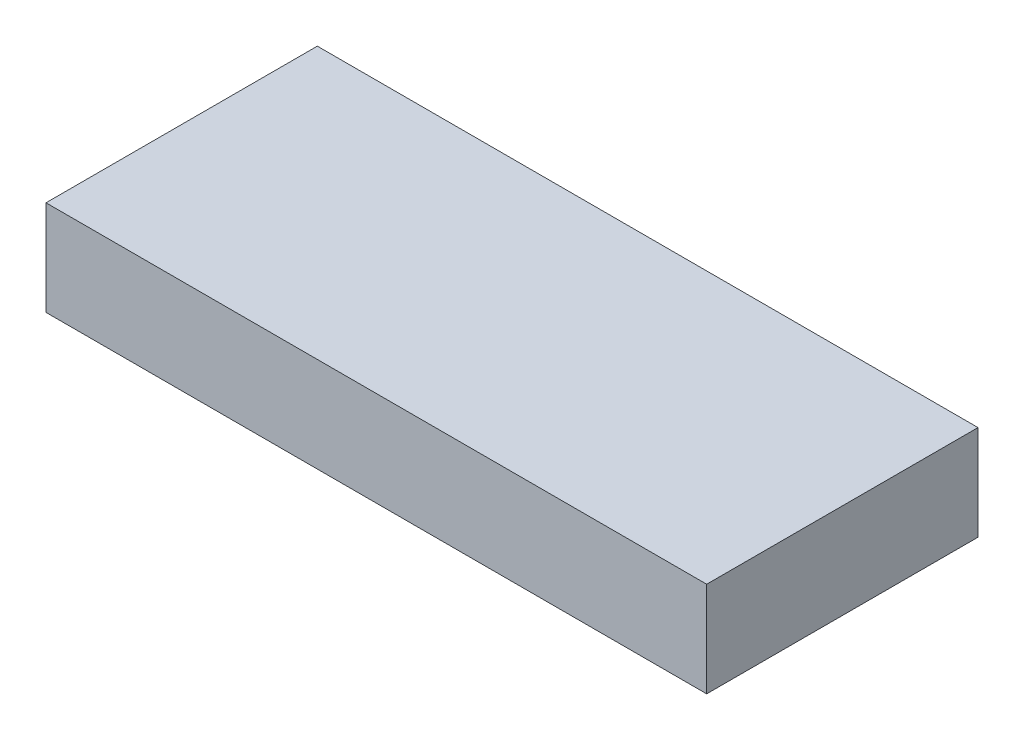
SolidWorks part; units mm, degrees
ref_plane "Front Plane" through (0, 0, 0) normal (0, 0, 1) x (1, 0, 0)
ref_plane "Top Plane" through (0, 0, 0) normal (0, 1, 0) x (1, 0, 0)
ref_plane "Right Plane" through (0, 0, 0) normal (1, 0, 0) x (0, 0, -1)
sketch "Sketch1" plane through (0, 0, 0) normal (0, 1, 0) x (1, 0, 0)
  line L1 (0, 0) -> (37.1094, 0)
  line L2 (0, 0) -> (0, 15.24)
  line L3 (0, 15.24) -> (37.1094, 15.24)
  line L4 (37.1094, 0) -> (37.1094, 15.24)
  dimension "D1" = 37.1094
  dimension "D2" = 15.24
extrude "Boss-Extrude1" add sketch "Sketch1" along normal blind 5.334
